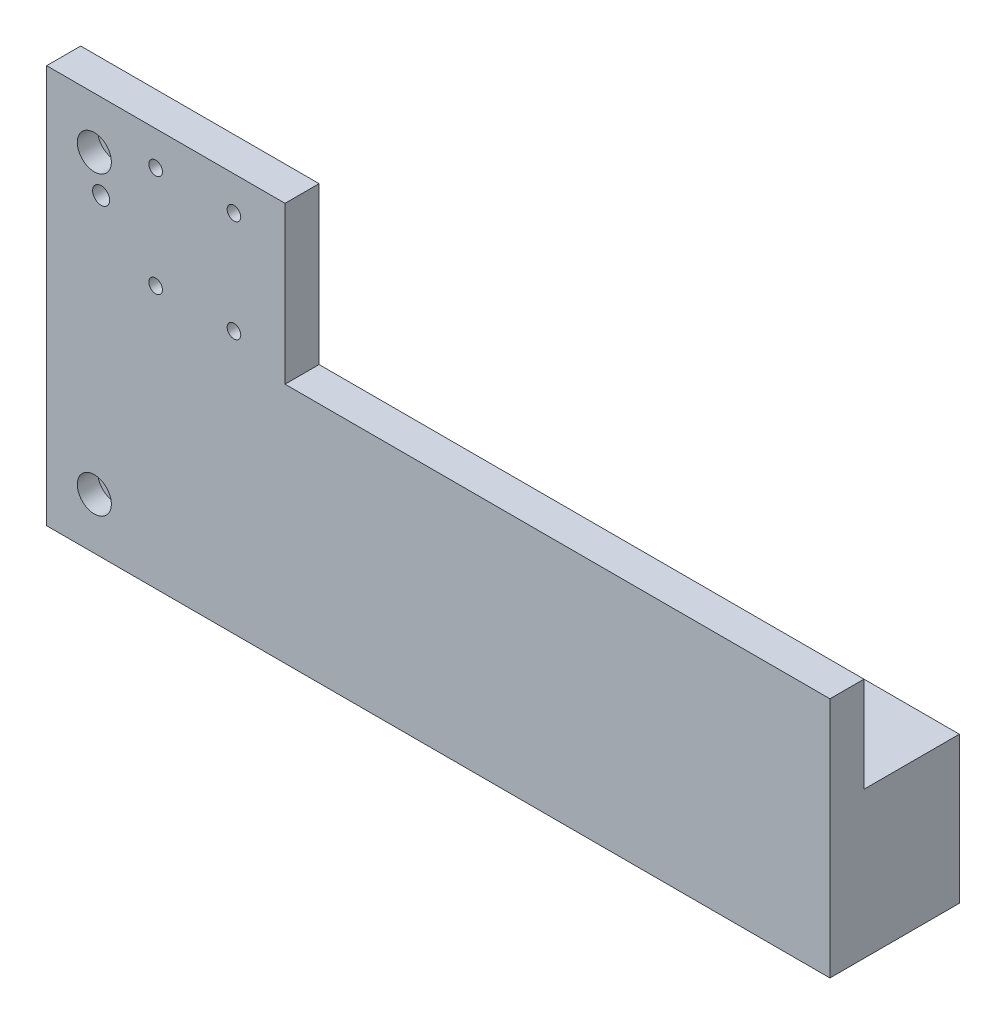
SolidWorks part; units mm, degrees
ref_plane "Ön Düzlem" through (0, 0, 0) normal (0, 0, 1) x (1, 0, 0)
ref_plane "Üst Düzlem" through (0, 0, 0) normal (0, 1, 0) x (1, 0, 0)
ref_plane "Sağ Düzlem" through (0, 0, 0) normal (1, 0, 0) x (0, 0, -1)
sketch "Sketch2" plane through (0, 0, 0) normal (0, 0, 1) x (1, 0, 0)
  line L1 (0, 0) -> (230, 0)
  line L2 (0, 0) -> (0, -120)
  line L3 (0, -120) -> (230, -120)
  line L4 (230, 0) -> (230, -120)
  dimension "D1" = 230
  dimension "D2" = 120
extrude "Boss-Extrude1" add sketch "Sketch2" along normal blind 38
sketch "Sketch3" plane through (0, 0, 38) normal (0, 0, 1) x (1, 0, 0)
  line L0 (28, -120) -> (28, -74)
  line L1 (0, -120) -> (230, -120) construction
  line L2 (28, -74) -> (230, -74)
  line L3 (230, -120) -> (230, 0) construction
  line L5 (0, 0) -> (230, 0)
  line L6 (0, 0) -> (0, -120)
  line L7 (0, -120) -> (28, -120)
  line L8 (230, 0) -> (230, -74)
  dimension "D1" = 46
  dimension "D2" = 28
extrude "Cut-Extrude1" cut sketch "Sketch3" against normal blind 28
sketch "Sketch4" plane through (0, 0, 10) normal (0, 0, 1) x (1, 0, 0)
  line L0 (28, -74) -> (230, -74) construction
  line L1 (230, 0) -> (70, 0)
  line L2 (230, 0) -> (230, -46)
  line L3 (230, -46) -> (70, -46)
  line L4 (70, 0) -> (70, -46)
  line L5 (230, -120) -> (230, -74) construction
  dimension "D1" = 28
  dimension "D2" = 160
extrude "Cut-Extrude2" cut sketch "Sketch4" against normal through all
mirror "Mirror1" [suppressed]
mirror "Mirror2" of bodies 108
delete or keep bodies "Body-Delete/Keep 1" type delete bodies bodies 108
sketch "Sketch5" plane through (0, -74, 0) normal (0, 1, 0) x (1, 0, 0)
  line L0 (28, 38) -> (230, 38) construction
  line L1 (28, 10) -> (28, 38) construction
  circle A0 centre (128, 24) radius 3
  dimension "D3" = 6
  dimension "D1" = 14
  dimension "D2" = 100
extrude "Cut-Extrude3" cut sketch "Sketch5" against normal blind 10
sketch "Sketch9" plane through (0, 0, -38) normal (0, 0, -1) x (-1, 0, 0)
  line L1 (-256.7129, -171.9764) -> (20.0265, -171.9764)
  line L2 (-256.7129, -171.9764) -> (-256.7129, -117)
  line L3 (-256.7129, -117) -> (20.0265, -117)
  line L4 (20.0265, -171.9764) -> (20.0265, -117)
  line L5 (-70, 0) -> (0, 0) construction
  dimension "D1" = 117
extrude "Cut-Extrude5" cut sketch "Sketch9" against normal through all
sketch "Sketch6" plane through (0, 0, -10) normal (0, 0, -1) x (-1, 0, 0)
  line L0 (-70, 0) -> (0, 0) construction
  line L2 (0, 0) -> (0, -117) construction
  line L3 (0, -117) -> (-28, -117) construction
  circle A0 centre (-14, -102) radius 3
  circle A1 centre (-14, -15) radius 3
  dimension "D3" = 14
  dimension "D4" = 6
  dimension "D1" = 15
  dimension "D2" = 15
extrude "Cut-Extrude4" cut sketch "Sketch6" against normal through all
sketch "Sketch10" plane through (0, 0, 0) normal (0, 0, 1) x (1, 0, 0)
  circle A0 centre (14, -15) radius 5
  circle A1 centre (14, -102) radius 5
  dimension "D1" = 10
extrude "Cut-Extrude6" cut sketch "Sketch10" against normal blind 6
sketch "Sketch11" plane through (0, 0, 0) normal (0, 0, 1) x (1, 0, 0)
  line L0 (0, 0) -> (0, -117) construction
  line L1 (32, -10) -> (55, -10) construction
  line L2 (32, -10) -> (32, -40) construction
  line L3 (32, -40) -> (55, -40) construction
  line L4 (55, -10) -> (55, -40) construction
  line L5 (32, -10) -> (55, -40) construction
  line L6 (32, -40) -> (55, -10) construction
  line L9 (70, 0) -> (0, 0) construction
  circle A0 centre (55, -40) radius 2
  circle A1 centre (55, -10) radius 2
  circle A2 centre (32, -10) radius 2
  circle A3 centre (32, -40) radius 2
  point P0 (43.5, -25)
  dimension "D2" = 55
  dimension "D3" = 32
  dimension "D4" = 4
  dimension "D5" = 40
  dimension "D1" = 30
extrude "Cut-Extrude7" cut sketch "Sketch11" against normal through all
sketch "Sketch12" plane through (0, 0, 0) normal (0, 0, 1) x (1, 0, 0)
  line L0 (0, 0) -> (0, -117) construction
  line L1 (70, 0) -> (0, 0) construction
  circle A0 centre (16, -25) radius 2.5
  dimension "D2" = 25
  dimension "D3" = 5
  dimension "D1" = 16
extrude "Cut-Extrude8" cut sketch "Sketch12" against normal through all
